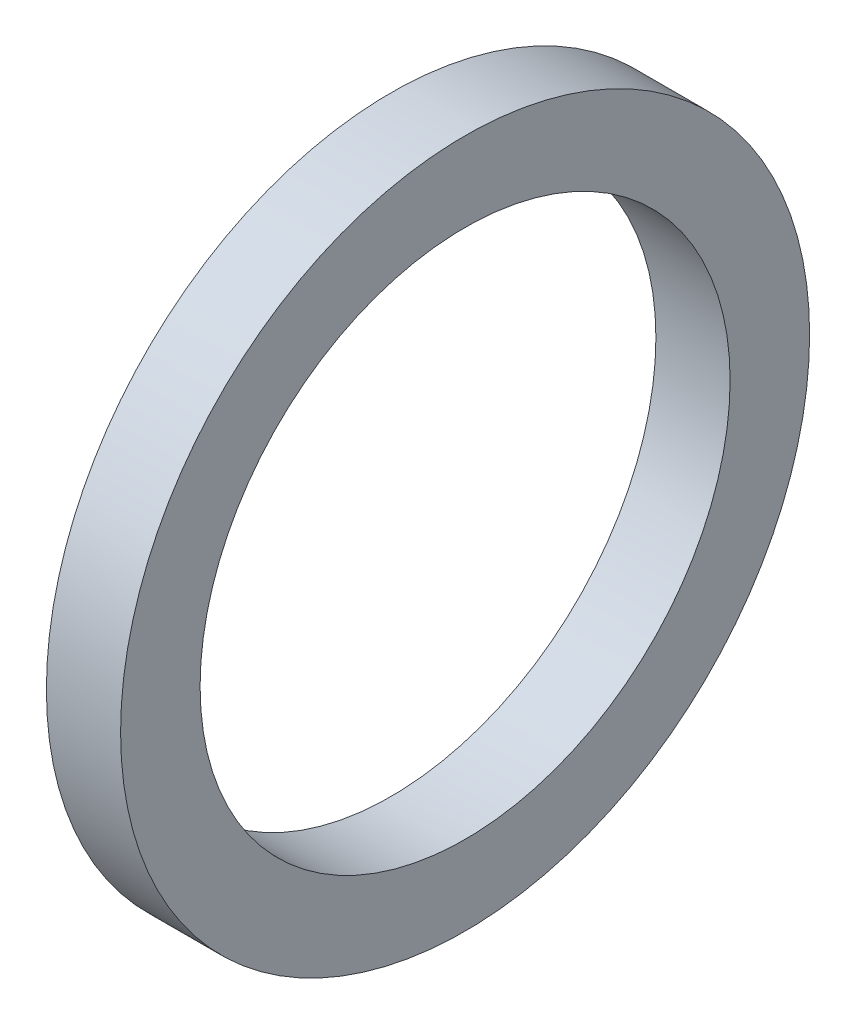
SolidWorks part; units mm, degrees
material "Plain Carbon Steel"
ref_plane "Front Plane" through (0, 0, 0) normal (0, 0, 1) x (1, 0, 0)
ref_plane "Top Plane" through (0, 0, 0) normal (0, 1, 0) x (1, 0, 0)
ref_plane "Right Plane" through (0, 0, 0) normal (1, 0, 0) x (0, 0, -1)
sketch "Sketch1" plane through (0, 0, 0) normal (1, 0, 0) x (0, 0, -1)
  circle A0 centre (0, 0) radius 32.5
  circle A1 centre (0, 0) radius 25
  dimension "D1" = 50
  dimension "D2" = 65
extrude "Boss-Extrude1" add sketch "Sketch1" along normal blind 7
